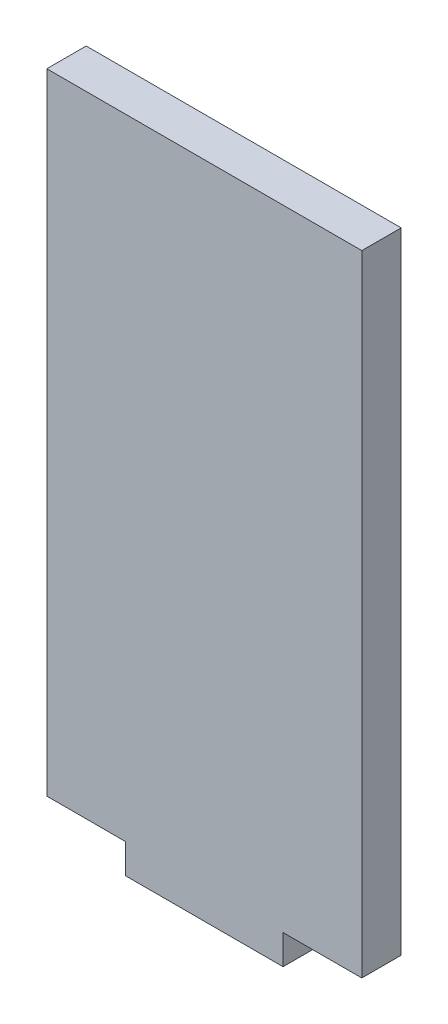
SolidWorks part; units mm, degrees
ref_plane "Front Plane" through (0, 0, 0) normal (0, 0, 1) x (1, 0, 0)
ref_plane "Top Plane" through (0, 0, 0) normal (0, 1, 0) x (1, 0, 0)
ref_plane "Right Plane" through (0, 0, 0) normal (1, 0, 0) x (0, 0, -1)
sketch "Sketch1" plane through (0, 0, 0) normal (0, 0, 1) x (1, 0, 0)
  line L0 (6.35, 0) -> (6.35, -2.3879)
  line L1 (0, 0) -> (6.35, 0)
  line L2 (0, 0) -> (0, 50.8)
  line L3 (0, 50.8) -> (25.4, 50.8)
  line L4 (25.4, 0) -> (25.4, 50.8)
  line L5 (6.35, -2.3879) -> (19.05, -2.3879)
  line L6 (19.05, -2.3879) -> (19.05, 0)
  line L7 (12.7, -2.3879) -> (12.7, 0) construction
  line L8 (19.05, 0) -> (25.4, 0)
  dimension "D1" = 25.4
  dimension "D2" = 50.8
  dimension "D3" = 12.7
extrude "Boss-Extrude1" add sketch "Sketch1" along normal blind 3.175
